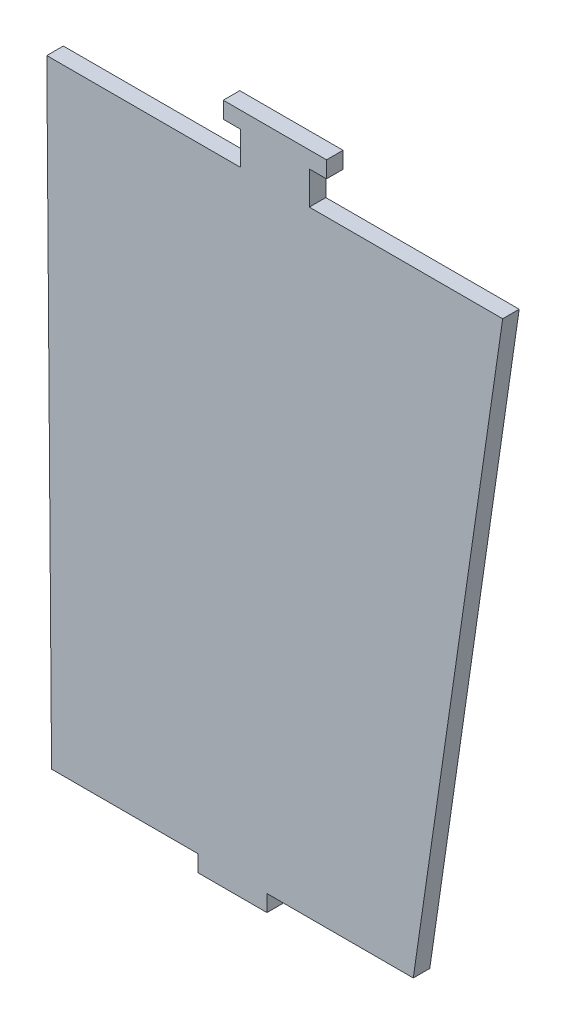
SolidWorks part; units mm, degrees
ref_plane "Front Plane" through (0, 0, 0) normal (0, 0, 1) x (1, 0, 0)
ref_plane "Top Plane" through (0, 0, 0) normal (0, 1, 0) x (1, 0, 0)
ref_plane "Right Plane" through (0, 0, 0) normal (1, 0, 0) x (0, 0, -1)
sketch "Sketch1" plane through (0, 0, 0) normal (0, 0, 1) x (1, 0, 0)
  line L0 (-102.4778, -1.524) -> (-110.7264, -58.3143) construction
  line L1 (-105.0444, -1.524) -> (-113.293, -58.3143)
  line L2 (-113.293, -58.3143) -> (-126.7879, -58.3143)
  line L3 (-149.1994, -58.3143) -> (-149.6393, -1.524) construction
  line L4 (-147.0992, -1.524) -> (-129.2335, -1.524)
  line L5 (-126.0585, -1.524) -> (-126.0585, 1.524) construction
  line L6 (-133.1379, -58.3143) -> (-133.1379, -59.8383)
  line L7 (-126.7879, -58.3143) -> (-126.7879, -59.8383)
  line L8 (-122.8835, -1.524) -> (-122.8835, 1.524)
  line L9 (-133.1379, -59.8383) -> (-126.7879, -59.8383)
  line L10 (-133.1379, -58.3143) -> (-146.6593, -58.3143)
  line L11 (-129.2335, -1.524) -> (-129.2335, 1.524)
  line L12 (-146.6593, -58.3143) -> (-147.0992, -1.524)
  line L13 (-129.2335, 1.524) -> (-130.821, 1.524)
  line L14 (-122.8835, -1.524) -> (-105.0444, -1.524)
  line L15 (-146.6595, -58.2947) -> (-147.0994, -1.5043) construction
  line L16 (-104.9914, -1.1589) -> (-113.24, -57.9492) construction
  line L18 (-121.296, 1.524) -> (-121.296, 3.048)
  line L19 (-130.821, 1.524) -> (-130.821, 3.048)
  line L20 (-121.296, 1.524) -> (-122.8835, 1.524)
  line L21 (-121.296, 3.048) -> (-130.821, 3.048)
extrude "Boss-Extrude1" add sketch "Sketch1" along normal blind 1.524
